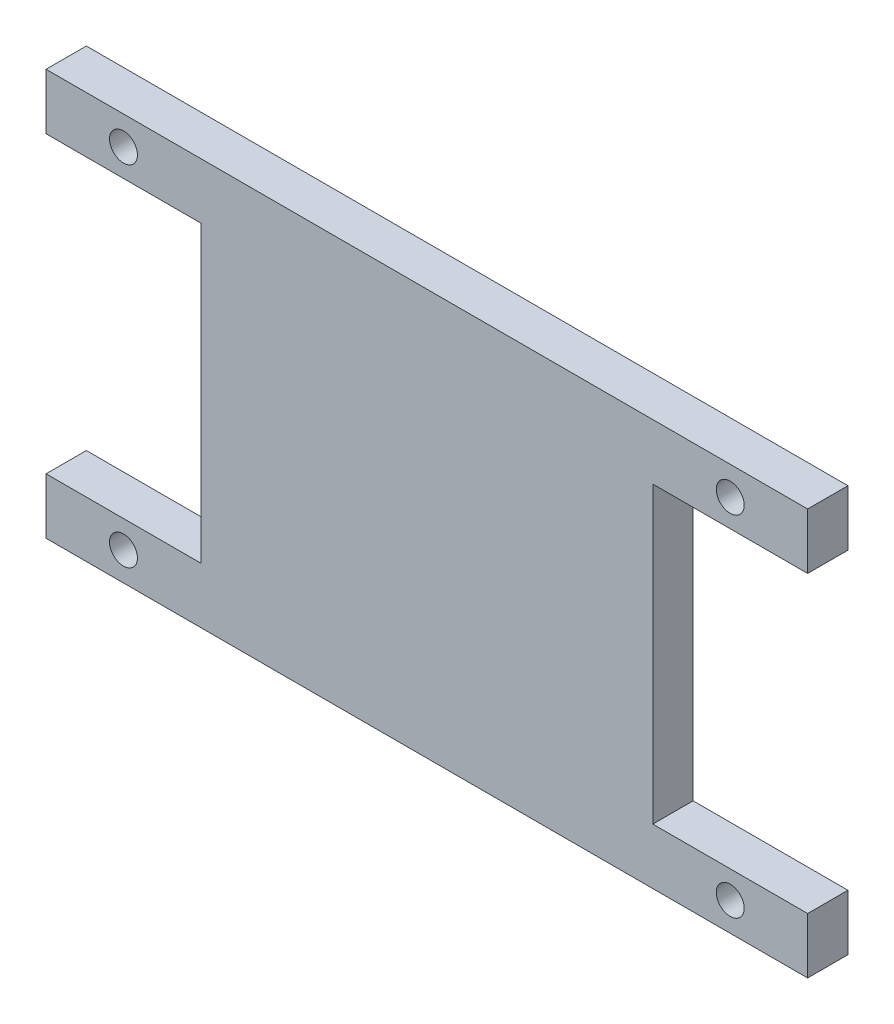
SolidWorks part; units mm, degrees
ref_plane "Front Plane" through (0, 0, 0) normal (0, 0, 1) x (1, 0, 0)
ref_plane "Top Plane" through (0, 0, 0) normal (0, 1, 0) x (1, 0, 0)
ref_plane "Right Plane" through (0, 0, 0) normal (1, 0, 0) x (0, 0, -1)
sketch "Sketch1" plane through (0, 0, 0) normal (0, 0, 1) x (1, 0, 0)
  line L1 (0, 0) -> (60, 0)
  line L2 (0, 0) -> (0, 32)
  line L3 (0, 32) -> (60, 32)
  line L4 (60, 0) -> (60, 32)
  line L5 (0, 27.6) -> (12.2, 27.6)
  line L6 (0, 27.6) -> (0, 4.4)
  line L7 (0, 4.4) -> (12.2, 4.4)
  line L8 (12.2, 27.6) -> (12.2, 4.4)
  line L9 (60, 27.6) -> (47.8, 27.6)
  line L10 (60, 27.6) -> (60, 4.4)
  line L11 (60, 4.4) -> (47.8, 4.4)
  line L12 (47.8, 27.6) -> (47.8, 4.4)
  circle A0 centre (6.1, 29.75) radius 1.1
  circle A1 centre (6.1, 2.25) radius 1.1
  circle A2 centre (53.9, 29.75) radius 1.1
  circle A3 centre (53.9, 2.25) radius 1.1
  dimension "D8" = 2.2
  dimension "D9" = 2.2
  dimension "D15" = 2.2
  dimension "D18" = 2.2
  dimension "D1" = 32
  dimension "D2" = 60
  dimension "D3" = 23.2
  dimension "D4" = 4.4
  dimension "D5" = 12.2
  dimension "D6" = 27.5
  dimension "D7" = 6.1
  dimension "D10" = 2.25
  dimension "D11" = 23.2
  dimension "D12" = 12.2
  dimension "D13" = 6.1
  dimension "D14" = 4.4
  dimension "D16" = 2.25
  dimension "D17" = 27.5
extrude "Boss-Extrude1" add sketch "Sketch1" along normal blind 3.175 contours L12 L9 L4 L3 L2 L5 L8 L7 L1 L11 A3 A2 A1 A0
